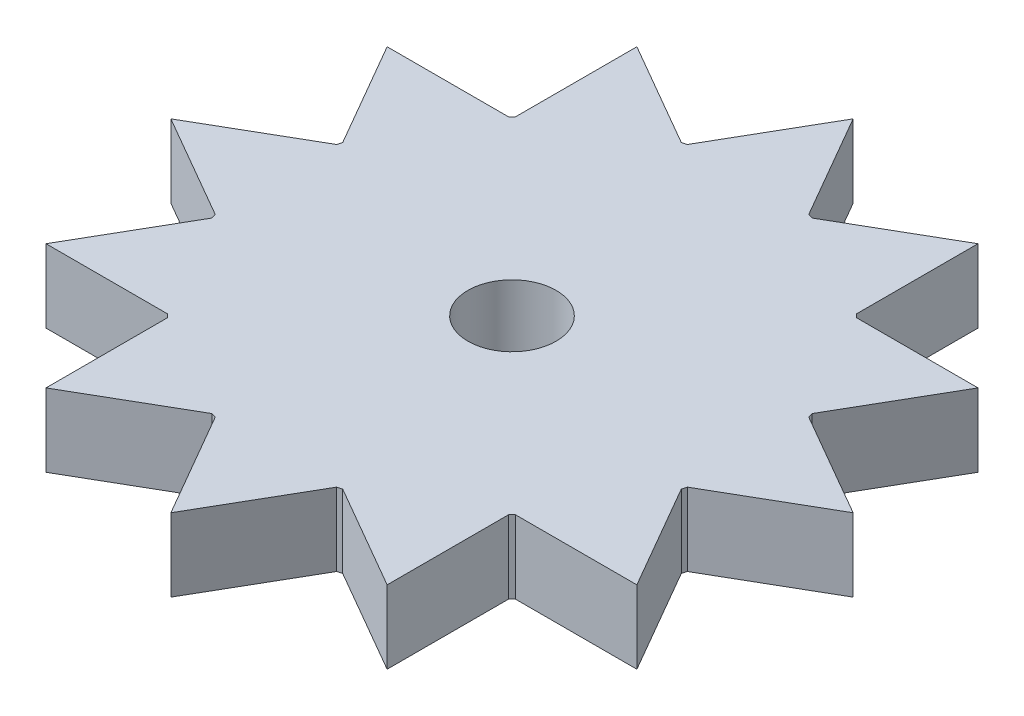
SolidWorks part; units mm, degrees
ref_plane "Front Plane" through (0, 0, 0) normal (0, 0, 1) x (1, 0, 0)
ref_plane "Top Plane" through (0, 0, 0) normal (0, 1, 0) x (1, 0, 0)
ref_plane "Right Plane" through (0, 0, 0) normal (1, 0, 0) x (0, 0, -1)
sketch "Sketch1" plane through (0, 0, 0) normal (0, 1, 0) x (1, 0, 0)
  circle A0 centre (0, 0) radius 10
  dimension "D1" = 20
extrude "Boss-Extrude1" add sketch "Sketch1" along normal blind 3
sketch "Sketch2" plane through (0, 3, 0) normal (0, 1, 0) x (1, 0, 0)
  line L0 (0, 10) -> (0, 14) construction
  line L24 (0, 14) -> (-2.4915, 9.6847)
  line L25 (-2.4915, 9.6847) -> (2.4915, 9.6847)
  line L26 (2.4915, 9.6847) -> (0, 14)
  circle A0 centre (0, 0) radius 10 construction
  point P55 (0, 0)
  dimension "D1" = 4
  dimension "D2" = 10
extrude "Boss-Extrude2" add sketch "Sketch2" against normal blind 3
pattern_circular "CirPattern1" count 12 over 360 about axis through (0, 0, 0) along (0, 1, 0) of "Boss-Extrude2"
sketch "Sketch3" plane through (0, 3, 0) normal (0, 1, 0) x (1, 0, 0)
  circle A0 centre (0, 0) radius 1.81
  dimension "D1" = 3.62
extrude "Cut-Extrude1" cut sketch "Sketch3" against normal blind 3
equation "\"Big_Teeth\"= 24"
equation "\"Small_Teeth\"= 12"
equation "\"Kerf\"= 0.18mm"
equation "\"D1@Sketch3\"=3.8-\"Kerf\""
